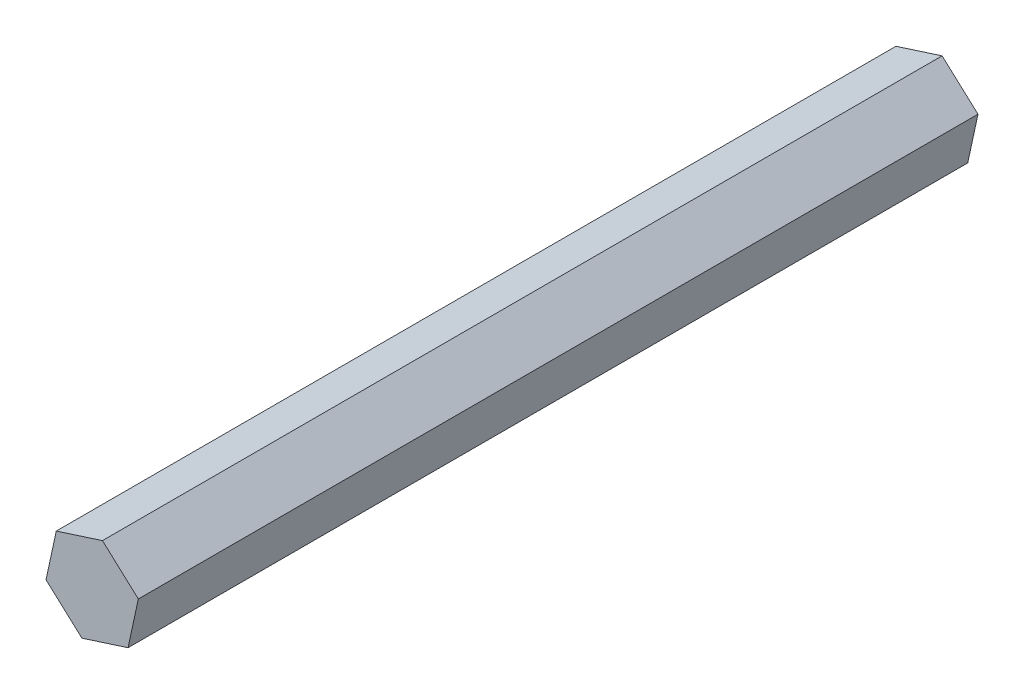
SolidWorks part; units mm, degrees
ref_plane "Front Plane" through (0, 0, 0) normal (0, 0, 1) x (1, 0, 0)
ref_plane "Top Plane" through (0, 0, 0) normal (0, 1, 0) x (1, 0, 0)
ref_plane "Right Plane" through (0, 0, 0) normal (1, 0, 0) x (0, 0, -1)
sketch "Sketch1" plane through (0, 0, 0) normal (0, 0, 1) x (1, 0, 0)
  line L1 (2.1373, -1.9404) -> (2.7491, 0.8807)
  line L2 (2.7491, 0.8807) -> (0.6118, 2.8212)
  line L3 (0.6118, 2.8212) -> (-2.1373, 1.9404)
  line L4 (-2.1373, 1.9404) -> (-2.7491, -0.8807)
  line L5 (-2.7491, -0.8807) -> (-0.6118, -2.8212)
  line L6 (-0.6118, -2.8212) -> (2.1373, -1.9404)
  circle A0 centre (0, 0) radius 2.5 construction
extrude "Boss-Extrude1" add sketch "Sketch1" along normal blind 50
